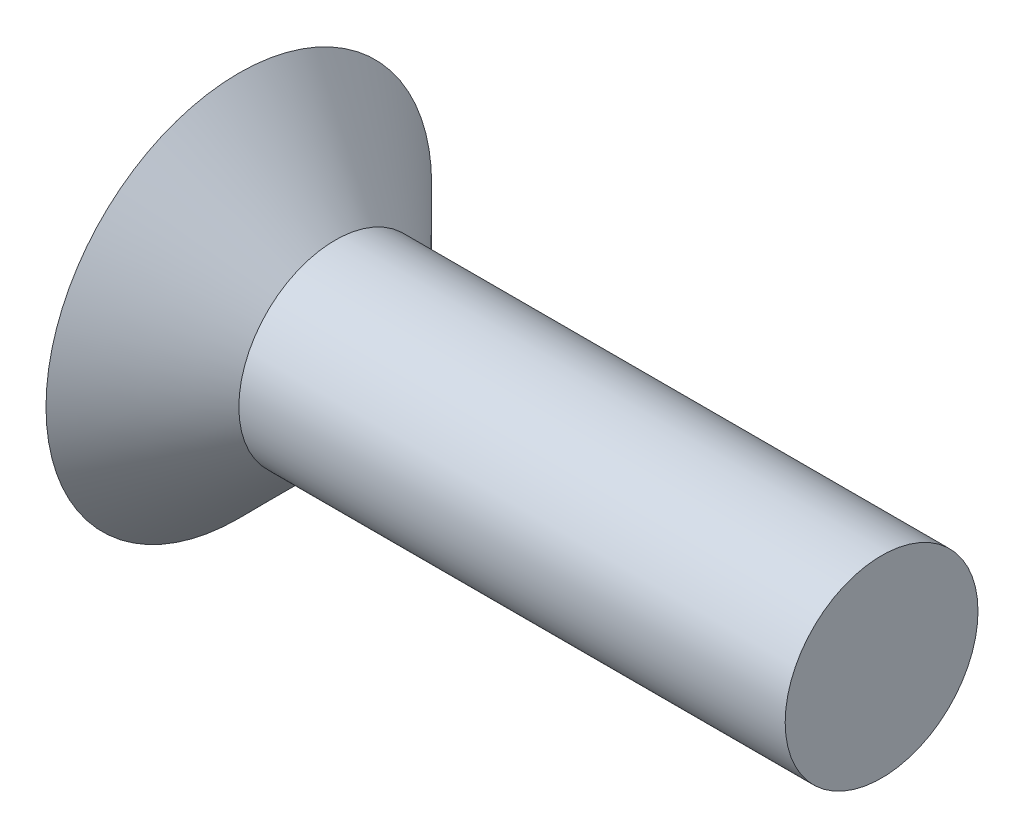
SolidWorks part; units mm, degrees
material "普通碳钢"
ref_plane "前视基准面" through (0, 0, 0) normal (0, 0, 1) x (1, 0, 0)
ref_plane "上视基准面" through (0, 0, 0) normal (0, 1, 0) x (1, 0, 0)
ref_plane "右视基准面" through (0, 0, 0) normal (1, 0, 0) x (0, 0, -1)
sketch "草图1" plane through (0, 0, 0) normal (0, 0, 1) x (1, 0, 0)
  line L0 (0, 0) -> (0, 3)
  line L5 (0, 0) -> (10, 0) construction
  line L6 (10, 0) -> (10, 1.5)
  line L7 (10, 1.5) -> (1.5, 1.5)
  line L8 (1.5, 1.5) -> (0, 3)
  dimension "D1" = 3
  dimension "D2" = 10
  dimension "D3" = 6
  dimension "D5" = 45
revolve "旋转1" add sketch "草图1" angle 360 about L5
cosmetic thread "装饰螺纹线2" parameters "D2"=1.221
sketch "草图2" plane through (0, 0, 0) normal (-1, 0, 0) x (0, 0, 1)
  line L1 (0, 1.1547) -> (-1, 0.5774)
  line L2 (-1, 0.5774) -> (-1, -0.5774)
  line L3 (-1, -0.5774) -> (0, -1.1547)
  line L4 (0, -1.1547) -> (1, -0.5774)
  line L5 (1, -0.5774) -> (1, 0.5774)
  line L6 (1, 0.5774) -> (0, 1.1547)
  circle A0 centre (0, 0) radius 1 construction
  dimension "D1" = 1
extrude "切除-拉伸1" cut sketch "草图2" against normal blind 1
